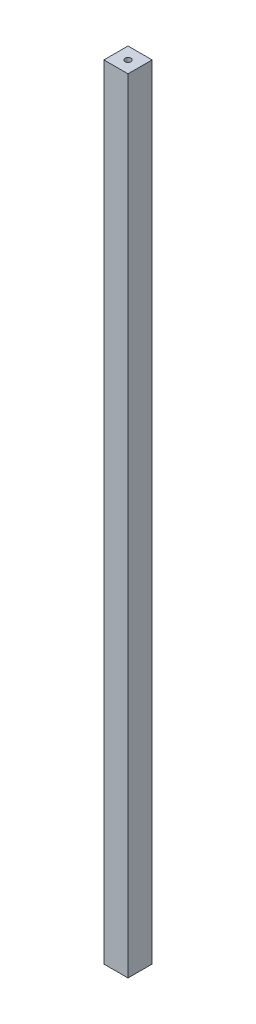
SolidWorks part; units mm, degrees
ref_plane "Front Plane" through (0, 0, 0) normal (0, 0, 1) x (1, 0, 0)
ref_plane "Top Plane" through (0, 0, 0) normal (0, 1, 0) x (1, 0, 0)
ref_plane "Right Plane" through (0, 0, 0) normal (1, 0, 0) x (0, 0, -1)
sketch "Sketch1" plane through (0, 0, 0) normal (0, 1, 0) x (1, 0, 0)
  line L1 (10, -10) -> (-10, -10)
  line L2 (10, -10) -> (10, 10)
  line L3 (10, 10) -> (-10, 10)
  line L4 (-10, -10) -> (-10, 10)
  line L5 (10, -10) -> (-10, 10) construction
  line L6 (10, 10) -> (-10, -10) construction
  point P0 (0, 0)
  dimension "D1" = 20
  dimension "D2" = 20
extrude "Boss-Extrude1" add sketch "Sketch1" along normal blind 650
sketch "Sketch2" plane through (0, 650, 0) normal (0, 1, 0) x (1, 0, 0)
  circle A0 centre (0, 0) radius 2.5
extrude "Cut-Extrude1" cut sketch "Sketch2" against normal blind 800
